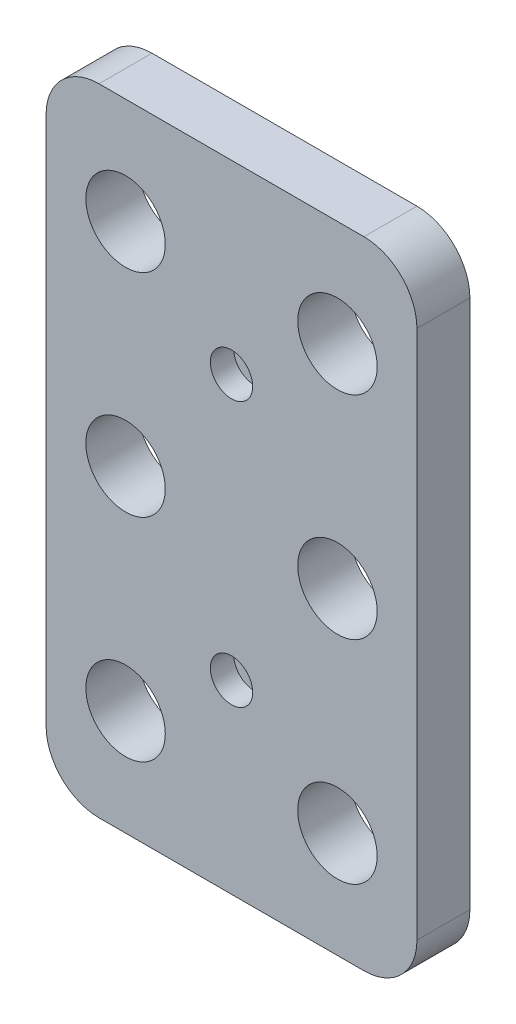
SolidWorks part; units mm, degrees
ref_plane "前视基准面" through (0, 0, 0) normal (0, 0, 1) x (1, 0, 0)
ref_plane "上视基准面" through (0, 0, 0) normal (0, 1, 0) x (1, 0, 0)
ref_plane "右视基准面" through (0, 0, 0) normal (1, 0, 0) x (0, 0, -1)
other "Configuration Table"
sketch "草图1" plane through (0, 0, 0) normal (0, 0, 1) x (1, 0, 0)
  line L0 (0, 60) -> (0, -60) construction
  line L1 (-25, -60) -> (25, -60)
  line L2 (-35, -50) -> (-35, 50)
  line L3 (-25, 60) -> (25, 60)
  line L4 (35, -50) -> (35, 50)
  line L5 (-35, -60) -> (35, 60) construction
  line L6 (-35, 60) -> (35, -60) construction
  line L7 (35, 0) -> (-35, 0) construction
  line L8 (35, 40) -> (-35, 40) construction
  arc A0 (-25, -60) -> (-35, -50) centre (-25, -50) cw
  arc A1 (25, -60) -> (35, -50) centre (25, -50) ccw
  arc A2 (25, 60) -> (35, 50) centre (25, 50) cw
  arc A3 (-35, 50) -> (-25, 60) centre (-25, 50) cw
  circle A4 centre (20, 40) radius 7.5
  circle A5 centre (20, 0) radius 7.5
  circle A6 centre (20, -40) radius 7.5
  circle A7 centre (-20, -40) radius 7.5
  circle A8 centre (-20, 0) radius 7.5
  circle A9 centre (-20, 40) radius 7.5
  circle A10 centre (0, 25) radius 2.25
  circle A11 centre (0, -25) radius 2.25
  point P0 (0, 0)
  dimension "D3" = 10
  dimension "D5" = 20
  dimension "D6" = 25
  dimension "D1" = 70
  dimension "D2" = 120
  dimension "D4" = 40
extrude "凸台-拉伸1" add sketch "草图1" along normal blind 10
sketch "草图2" plane through (0, 0, 10) normal (0, 0, 1) x (1, 0, 0)
  circle A0 centre (0, 25) radius 4
  circle A1 centre (0, -25) radius 4
extrude "切除-拉伸1" cut sketch "草图2" against normal blind 4.4
